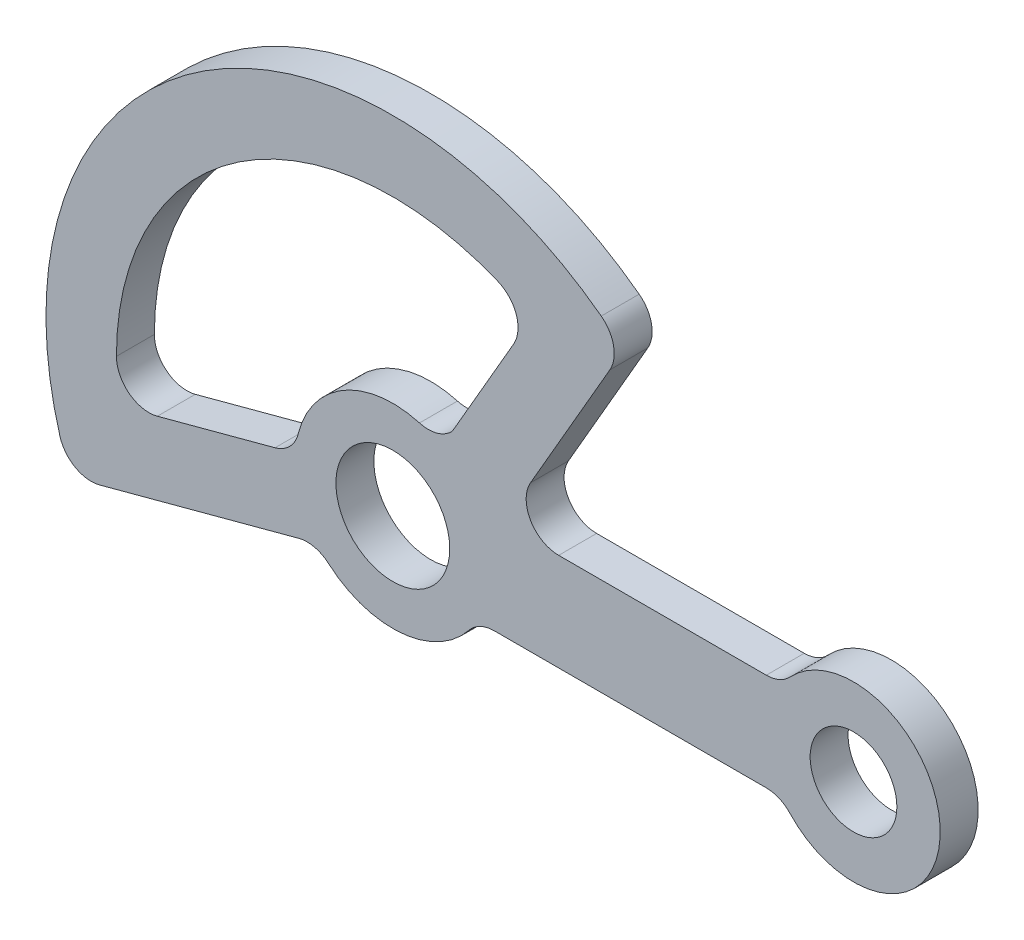
SolidWorks part; units mm, degrees
ref_plane "Front Plane" through (0, 0, 0) normal (0, 0, 1) x (1, 0, 0)
ref_plane "Top Plane" through (0, 0, 0) normal (0, 1, 0) x (1, 0, 0)
ref_plane "Right Plane" through (0, 0, 0) normal (1, 0, 0) x (0, 0, -1)
sketch "Sketch2" plane through (0, 0, 0) normal (0, 0, 1) x (1, 0, 0)
  line L0 (0, 0) -> (-64, 0) construction
  line L1 (-21.731, 0.0232) -> (-43.4471, -5.7956)
  line L2 (0, 0) -> (0, 72.1576) construction
  line L3 (5.1962, 9) -> (5.25, 9.0933)
  line L4 (10.9887, 19.0331) -> (22.2991, 38.6232)
  line L5 (-17.3596, -12.264) -> (-54.1053, -22.11)
  line L6 (25.4034, 18) -> (40.0463, 43.3623)
  line L7 (0, 0) -> (85, 0) construction
  line L8 (18.735, -9) -> (68.9065, -9)
  line L9 (5.1962, 9) -> (5.4083, 9)
  line L10 (0, 9) -> (85, 9) construction
  line L11 (30.5996, 9) -> (68.9065, 9)
  line L12 (0, -9) -> (85, -9) construction
  circle A0 centre (0, 0) radius 10.5
  arc A1 (-11.855, -13.5447) -> (14.0512, -11.25) centre (0, 0) ccw
  arc A4 (38.4554, 51.1584) -> (-61.416, -18.0022) centre (0, 0) ccw
  arc A6 (-51, 0) -> (-43.4471, -5.7956) centre (-45, 0) ccw
  arc A7 (-21.731, 0.0232) -> (-17.4629, 4.3641) centre (-23.2839, 5.8188) ccw
  arc A8 (22.2991, 38.6232) -> (19.3833, 47.1729) centre (17.103, 41.6232) ccw
  arc A9 (10.9887, 19.0331) -> (4.9227, 17.3138) centre (6.5636, 23.085) cw
  arc A10 (-17.3596, -12.264) -> (-11.855, -13.5447) centre (-15.8067, -18.0596) cw
  arc A11 (-61.416, -18.0022) -> (-54.1053, -22.11) centre (-55.6582, -16.3145) ccw
  arc A12 (19.3833, 47.1729) -> (-51, 0) centre (0, 0) ccw
  arc A13 (38.4554, 51.1584) -> (-61.416, -18.0022) centre (0, 0) ccw
  arc A14 (40.0463, 43.3623) -> (38.4554, 51.1584) centre (34.8502, 46.3623) ccw
  circle A15 centre (85, 0) radius 8
  arc A16 (73.2957, -10.9091) -> (73.2957, 10.9091) centre (85, 0) ccw
  arc A17 (68.9065, 9) -> (73.2957, 10.9091) centre (68.9065, 15) ccw
  arc A18 (68.9065, -9) -> (73.2957, -10.9091) centre (68.9065, -15) cw
  arc A19 (30.5996, 9) -> (25.4034, 18) centre (30.5996, 15) cw
  arc A20 (4.9227, 17.3138) -> (-17.4629, 4.3641) centre (0, 0) ccw
  arc A21 (18.735, -9) -> (14.0512, -11.25) centre (18.735, -15) ccw
  point P14 (0, 0)
  dimension "D1" = 21
  dimension "D4" = 6
  dimension "D5" = 6
  dimension "D7" = 51
  dimension "D8" = 128
  dimension "D9" = 6
  dimension "D10" = 6
  dimension "D12" = 6
  dimension "D13" = 6
  dimension "D15" = 9
  dimension "D14" = 13
  dimension "D16" = 32
  dimension "D17" = 16
  dimension "D18" = 6
  dimension "D19" = 6
  dimension "D20" = 6
  dimension "D22" = 18
  dimension "D23" = 6
  dimension "D3" = 15
  dimension "D6" = 30
  dimension "D11" = 13
  dimension "D21" = 85
extrude "Boss-Extrude2" add sketch "Sketch2" along normal blind 7 contours A21 L8 A18 A16 A17 L11 A19 L6 A14 A4 A11 L5 A10 A1 A15 A0 A9 A20 A7 L1 A6 A12 A8 L4
